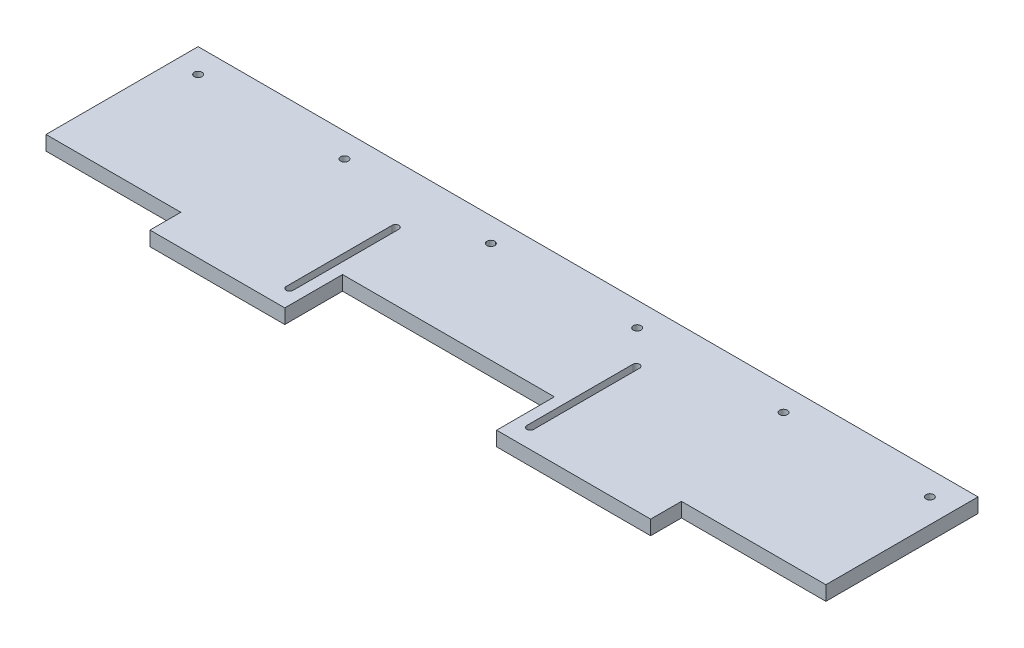
SolidWorks part; units mm, degrees
material "Acrylic (Medium-high impact)"
ref_plane "Front Plane" through (0, 0, 0) normal (0, 0, 1) x (1, 0, 0)
ref_plane "Top Plane" through (0, 0, 0) normal (0, 1, 0) x (1, 0, 0)
ref_plane "Right Plane" through (0, 0, 0) normal (1, 0, 0) x (0, 0, -1)
sketch "Sketch1" plane through (0, 0, 0) normal (0, 1, 0) x (1, 0, 0)
  line L1 (-250.825, -28.575) -> (250.825, -28.575)
  line L2 (-250.825, -28.575) -> (-250.825, 28.575)
  line L3 (-250.825, 28.575) -> (250.825, 28.575)
  line L4 (250.825, -28.575) -> (250.825, 28.575)
  line L5 (-250.825, -28.575) -> (250.825, 28.575) construction
  line L6 (-250.825, 28.575) -> (250.825, -28.575) construction
  line L7 (174.625, -28.575) -> (-28.575, -28.575)
  line L11 (-282.575, -28.575) -> (-130.175, -28.575)
  point P0 (0, 0)
  dimension "D1" = 501.65
  dimension "D2" = 57.15
extrude "Boss-Extrude1" add sketch "Sketch1" along normal mid plane 9.525 contours L1 L4 L3 L2
sketch "Sketch2" plane through (0, 0, 0) normal (0, 1, 0) x (1, 0, 0)
  line L0 (-250.825, -28.575) -> (250.825, -28.575) construction
  line L1 (161.925, -28.575) -> (60.325, -28.575)
  line L2 (161.925, -28.575) -> (161.925, -92.075)
  line L3 (161.925, -92.075) -> (60.325, -92.075)
  line L4 (60.325, -28.575) -> (60.325, -92.075)
  line L5 (0, -5.2388) -> (0, 5.2388) construction
  line L6 (-79.375, -28.575) -> (-168.275, -28.575)
  line L7 (-79.375, -28.575) -> (-79.375, -92.075)
  line L8 (-79.375, -92.075) -> (-168.275, -92.075)
  line L9 (-168.275, -28.575) -> (-168.275, -92.075)
  line L10 (250.825, -28.575) -> (250.825, 28.575) construction
  line L11 (-250.825, -28.575) -> (-250.825, 28.575) construction
  line L12 (-250.825, 28.575) -> (250.825, 28.575) construction
  line L13 (250.825, -28.575) -> (250.825, 28.575) construction
  line L14 (161.925, -28.575) -> (250.825, -28.575)
  line L15 (161.925, -28.575) -> (161.925, -71.755)
  line L16 (161.925, -71.755) -> (250.825, -71.755)
  line L17 (250.825, -28.575) -> (250.825, -71.755)
  line L18 (-250.825, -28.575) -> (-250.825, 28.575) construction
  line L19 (-79.375, -28.575) -> (60.325, -28.575)
  line L20 (-79.375, -28.575) -> (-79.375, -53.975)
  line L21 (-79.375, -53.975) -> (60.325, -53.975)
  line L22 (60.325, -28.575) -> (60.325, -53.975)
  line L23 (-168.275, -28.575) -> (-250.825, -28.575)
  line L24 (-168.275, -28.575) -> (-168.275, -71.755)
  line L25 (-168.275, -71.755) -> (-250.825, -71.755)
  line L26 (-250.825, -28.575) -> (-250.825, -71.755)
  point P19 (60.325, -92.075)
  dimension "D1" = 139.7
  dimension "D2" = 88.9
  dimension "D3" = 82.55
  dimension "D4" = 79.375
  dimension "D5" = 120.65
  dimension "D6" = 43.18
  dimension "D7" = 25.4
  dimension "D8" = 43.18
extrude "Boss-Extrude2" add sketch "Sketch2" along normal mid plane 9.525 contours L6 L9 L8 L7 | L23 L26 L25 L9 | L7 L21 L4 L19 | L17 L14 L2 L16
sketch "Sketch3" [suppressed] plane through (0, 4.7625, 0) normal (0, 1, 0) x (1, 0, 0)
  line L0 (-149.225, 247.65) -> (149.225, 247.65) construction
  line L1 (-98.425, 12.7) -> (98.425, 12.7)
  line L2 (-98.425, 12.7) -> (-98.425, -101.6)
  line L3 (-98.425, -101.6) -> (98.425, -101.6)
  line L4 (98.425, 12.7) -> (98.425, -101.6)
  line L5 (-98.425, 12.7) -> (98.425, -101.6) construction
  line L6 (-98.425, -101.6) -> (98.425, 12.7) construction
  line L7 (-149.225, -247.65) -> (149.225, -247.65) construction
  point P0 (0, -44.45)
  point P7 (0, 247.65)
  point P8 (0, 12.7)
  dimension "D1" = 196.85
  dimension "D2" = 114.3
  dimension "D3" = 203.2
extrude "Cut-Extrude1" [suppressed] cut sketch "Sketch3" against normal through all and the other way through all
sketch "Sketch4" [suppressed] plane through (0, -4.7625, 0) normal (0, -1, 0) x (1, 0, 0)
  line L0 (-107.315, 31.75) -> (107.315, 31.75) construction
  line L1 (-107.315, 33.9979) -> (107.315, 33.9979)
  line L2 (-107.315, 29.5021) -> (107.315, 29.5021)
  line L3 (-107.315, 6.35) -> (107.315, 6.35) construction
  line L4 (-107.315, 8.5979) -> (107.315, 8.5979)
  line L5 (-107.315, 4.1021) -> (107.315, 4.1021)
  arc A0 (-107.315, 33.9979) -> (-107.315, 29.5021) centre (-107.315, 31.75) ccw
  arc A1 (107.315, 29.5021) -> (107.315, 33.9979) centre (107.315, 31.75) ccw
  arc A2 (-107.315, 8.5979) -> (-107.315, 4.1021) centre (-107.315, 6.35) ccw
  arc A3 (107.315, 4.1021) -> (107.315, 8.5979) centre (107.315, 6.35) ccw
  point P0 (-107.315, 31.75)
  point P1 (107.315, 31.75)
  point P3 (107.315, 6.35)
  point P5 (-107.315, 6.35)
  point P10 (0, 31.75)
  point P15 (0, 6.35)
  dimension "D1" = 4.4958
  dimension "D2" = 4.4958
extrude "Cut-Extrude2" [suppressed] cut sketch "Sketch4" against normal through all
sketch "Sketch5" plane through (0, -4.7625, 0) normal (0, -1, 0) x (1, 0, 0)
  line L0 (69.85, 79.375) -> (69.85, -9.525) construction
  line L1 (60.325, 53.975) -> (60.325, 92.075) construction
  line L2 (161.925, 92.075) -> (60.325, 92.075) construction
  line L3 (-247.65, -22.225) -> (247.65, -22.225) construction
  line L4 (69.85, 79.375) -> (69.85, -9.525) construction
  line L5 (72.0979, 79.375) -> (72.0979, -9.525)
  line L6 (67.6021, 79.375) -> (67.6021, -9.525)
  line L7 (-88.9, 79.375) -> (-88.9, -9.525) construction
  line L8 (-79.375, 53.975) -> (-79.375, 92.075) construction
  line L9 (-79.375, 92.075) -> (-168.275, 92.075) construction
  line L10 (-88.9, 79.375) -> (-88.9, -9.525) construction
  line L11 (-86.6521, 79.375) -> (-86.6521, -9.525)
  line L12 (-91.1479, 79.375) -> (-91.1479, -9.525)
  arc A0 (72.0979, 79.375) -> (67.6021, 79.375) centre (69.85, 79.375) ccw
  arc A1 (67.6021, -9.525) -> (72.0979, -9.525) centre (69.85, -9.525) ccw
  arc A2 (-86.6521, 79.375) -> (-91.1479, 79.375) centre (-88.9, 79.375) ccw
  arc A3 (-91.1479, -9.525) -> (-86.6521, -9.525) centre (-88.9, -9.525) ccw
  point P8 (69.85, 34.925)
  point P19 (-88.9, 34.925)
  dimension "D1" = 9.525
  dimension "D2" = 12.7
  dimension "D3" = 12.7
  dimension "D4" = 4.4958
  dimension "D5" = 9.525
  dimension "D6" = 12.7
  dimension "D7" = 12.7
  dimension "D8" = 4.4958
extrude "Cut-Extrude3" [suppressed] cut sketch "Sketch5" against normal through all contours L12 A3 L11 A2 | L6 A1 L5 A0
sketch "Sketch6" [suppressed] plane through (0, 3.175, 0) normal (0, 1, 0) x (1, 0, 0)
  line L0 (-79.375, -38.1) -> (-79.375, 38.1) construction
  line L1 (-88.9, -50.8) -> (-88.9, 50.8) construction
  line L2 (-88.9, -50.8) -> (88.9, -50.8) construction
  line L3 (-88.9, 50.8) -> (88.9, 50.8) construction
  line L4 (79.375, -38.1) -> (79.375, 38.1) construction
  line L5 (88.9, -50.8) -> (88.9, 50.8) construction
  line L6 (-79.375, -38.1) -> (-79.375, 38.1) construction
  line L7 (-81.6229, -38.1) -> (-81.6229, 38.1)
  line L8 (-77.1271, -38.1) -> (-77.1271, 38.1)
  line L9 (79.375, -38.1) -> (79.375, 38.1) construction
  line L10 (77.1271, -38.1) -> (77.1271, 38.1)
  line L11 (81.6229, -38.1) -> (81.6229, 38.1)
  arc A0 (-81.6229, -38.1) -> (-77.1271, -38.1) centre (-79.375, -38.1) ccw
  arc A1 (-77.1271, 38.1) -> (-81.6229, 38.1) centre (-79.375, 38.1) ccw
  arc A2 (77.1271, -38.1) -> (81.6229, -38.1) centre (79.375, -38.1) ccw
  arc A3 (81.6229, 38.1) -> (77.1271, 38.1) centre (79.375, 38.1) ccw
  point P12 (-79.375, 0)
  point P17 (79.375, 0)
  dimension "D1" = 9.525
  dimension "D2" = 12.7
  dimension "D3" = 12.7
  dimension "D4" = 9.525
  dimension "D5" = 12.7
  dimension "D6" = 12.7
  dimension "D7" = 4.4958
  dimension "D8" = 4.4958
extrude "Cut-Extrude4" [suppressed] cut sketch "Sketch6" against normal through all
sketch "Sketch7" [suppressed] plane through (0, 4.7625, 0) normal (0, 1, 0) x (1, 0, 0)
  point P0 (115.1313, 66.802)
  point P1 (139.827, 42.1063)
  point P3 (-139.827, 42.1063)
  point P5 (-115.1313, 66.802)
hole_wizard "#12 Clearance Hole1" [suppressed] positions "Sketch8" profile "Sketch9" hole size "#12" standard "ANSI Inch"
sketch "Sketch8" plane through (0, 4.7625, 0) normal (0, 1, 0) x (1, 0, 0)
  point P0 (-139.827, 42.1063)
  point P3 (-115.1313, 66.802)
  point P6 (115.1313, 66.802)
  point P9 (139.827, 42.1063)
sketch "Sketch9" plane through (-139.827, 4.7625, -42.1063) normal (1, 0, 0) x (0, 0, 1)
  line L0 (0, 0) -> (0, 18.1964)
  line L1 (0, 18.1964) -> (2.8067, 16.51)
  line L2 (2.8067, 16.51) -> (2.8067, 0)
  line L5 (2.8067, 0) -> (0, 0)
  line L10 (0, 18.1964) -> (-2.8067, 16.51) construction
  line L11 (0, -6.35) -> (0, 107.95) construction
  dimension "Hole Dia." = 5.6134
  dimension "Hole Depth" = 16.51
  dimension "Drill Angle" = 118
sketch "Sketch10" [suppressed] plane through (0, -4.7625, 0) normal (0, -1, 0) x (1, 0, 0)
  point P0 (223.8375, -6.35)
  point P1 (223.8375, 19.05)
  point P3 (-223.8375, 19.05)
  point P5 (-223.8375, -6.35)
hole_wizard "#12 Clearance Hole3" [suppressed] positions "Sketch11" profile "Sketch12" hole size "#12" standard "ANSI Inch"
sketch "Sketch11" [suppressed] plane through (0, -4.7625, 0) normal (0, -1, 0) x (-1, 0, 0)
  point P0 (-223.8375, -19.05)
  point P3 (-223.8375, 6.35)
  point P6 (223.8375, -19.05)
  point P9 (223.8375, 6.35)
sketch "Sketch12" plane through (223.8375, -4.7625, 19.05) normal (1, 0, 0) x (0, 0, -1)
  line L0 (0, 0) -> (0, 18.1964)
  line L1 (0, 18.1964) -> (2.8067, 16.51)
  line L2 (2.8067, 16.51) -> (2.8067, 0)
  line L5 (2.8067, 0) -> (0, 0)
  line L10 (0, 18.1964) -> (-2.8067, 16.51) construction
  line L11 (0, -6.35) -> (0, 107.95) construction
  dimension "Hole Dia." = 5.6134
  dimension "Hole Depth" = 16.51
  dimension "Drill Angle" = 118
sketch "Sketch13" [suppressed] plane through (0, -4.7625, 0) normal (0, -1, 0) x (1, 0, 0)
  point P0 (133.35, -223.8375)
  point P1 (107.95, -223.8375)
  point P3 (-107.95, -223.8375)
  point P5 (-133.35, -223.8375)
  point P7 (133.35, 223.8375)
  point P9 (107.95, 223.8375)
  point P11 (-107.95, 223.8375)
  point P13 (-133.35, 223.8375)
hole_wizard "#12 Clearance Hole2" [suppressed] positions "Sketch14" profile "Sketch15" hole size "#12" standard "ANSI Inch"
sketch "Sketch14" plane through (0, -4.7625, 0) normal (0, -1, 0) x (-1, 0, 0)
  point P0 (107.95, -223.8375)
  point P3 (133.35, -223.8375)
  point P6 (133.35, 223.8375)
  point P9 (107.95, 223.8375)
  point P12 (-133.35, 223.8375)
  point P15 (-107.95, 223.8375)
  point P18 (-133.35, -223.8375)
  point P21 (-107.95, -223.8375)
sketch "Sketch15" plane through (-107.95, -4.7625, 223.8375) normal (1, 0, 0) x (0, 0, -1)
  line L0 (0, 0) -> (0, 18.1964)
  line L1 (0, 18.1964) -> (2.8067, 16.51)
  line L2 (2.8067, 16.51) -> (2.8067, 0)
  line L5 (2.8067, 0) -> (0, 0)
  line L10 (0, 18.1964) -> (-2.8067, 16.51) construction
  line L11 (0, -6.35) -> (0, 107.95) construction
  dimension "Hole Dia." = 5.6134
  dimension "Hole Depth" = 16.51
  dimension "Drill Angle" = 118
sketch "Sketch16" [suppressed] plane through (0, 3.175, 0) normal (0, 1, 0) x (1, 0, 0)
  line L0 (88.9, -50.8) -> (88.9, 50.8) construction
  line L1 (-88.9, -50.8) -> (-88.9, 50.8) construction
  line L2 (-88.9, -50.8) -> (88.9, -50.8) construction
  point P0 (79.375, -38.1)
  point P1 (-79.375, -38.1)
  dimension "D1" = 9.525
  dimension "D2" = 9.525
  dimension "D3" = 12.7
hole_wizard "#8 Clearance Hole1" [suppressed] positions "Sketch17" profile "Sketch19" hole size "#8" standard "ANSI Inch"
sketch "Sketch17" plane through (0, 3.175, 0) normal (0, 1, 0) x (1, 0, 0)
  point P0 (79.375, -38.1)
  point P3 (-79.375, -38.1)
sketch "Sketch19" plane through (79.375, 3.175, 38.1) normal (1, 0, 0) x (0, 0, 1)
  line L0 (0, 0) -> (0, 12.0187)
  line L1 (0, 12.0187) -> (2.2479, 10.668)
  line L2 (2.2479, 10.668) -> (2.2479, 0)
  line L5 (2.2479, 0) -> (0, 0)
  line L10 (0, 12.0187) -> (-2.2479, 10.668) construction
  line L11 (0, -6.35) -> (0, 107.95) construction
  dimension "Hole Dia." = 4.4958
  dimension "Hole Depth" = 10.668
  dimension "Drill Angle" = 118
sketch "Sketch20" [suppressed] plane through (0, -4.7625, 0) normal (0, -1, 0) x (1, 0, 0)
  line L0 (-149.225, 247.65) -> (149.225, 247.65) construction
  line L1 (23.9395, 147.5105) -> (-23.9395, 147.5105)
  line L2 (23.9395, 147.5105) -> (23.9395, 195.3895)
  line L3 (23.9395, 195.3895) -> (-23.9395, 195.3895)
  line L4 (-23.9395, 147.5105) -> (-23.9395, 195.3895)
  line L5 (23.9395, 147.5105) -> (-23.9395, 195.3895) construction
  line L6 (23.9395, 195.3895) -> (-23.9395, 147.5105) construction
  line L8 (38.1, 155.575) -> (-38.1, 155.575) construction
  line L9 (38.1, 155.575) -> (38.1, 187.325) construction
  line L10 (38.1, 187.325) -> (-38.1, 187.325) construction
  line L11 (-38.1, 155.575) -> (-38.1, 187.325) construction
  point P0 (0, 171.45)
  point P7 (0, 247.65)
  point P8 (38.1, 155.575)
  point P9 (38.1, 187.325)
  point P10 (-38.1, 155.575)
  point P11 (-38.1, 187.325)
  point P18 (0, 187.325)
  point P19 (0, 195.3895)
  point P20 (-38.1, 171.45)
  point P21 (-23.9395, 171.45)
  dimension "D1" = 47.879
  dimension "D2" = 47.879
  dimension "D3" = 38.1
  dimension "D4" = 15.875
  dimension "D5" = 76.2
extrude "Cut-Extrude5" [suppressed] cut sketch "Sketch20" against normal through all contours L1 L4 L3 L2
hole_wizard "#10 Clearance Hole1" [suppressed] positions "Sketch21" profile "Sketch22" hole size "#10" standard "ANSI Inch"
sketch "Sketch21" plane through (0, -4.7625, 0) normal (0, -1, 0) x (-1, 0, 0)
  point P0 (-38.1, -155.575)
  point P3 (38.1, -155.575)
  point P6 (38.1, -187.325)
  point P9 (-38.1, -187.325)
sketch "Sketch22" plane through (38.1, -4.7625, 155.575) normal (1, 0, 0) x (0, 0, -1)
  line L0 (0, 0) -> (0, 12.2018)
  line L1 (0, 12.2018) -> (2.5527, 10.668)
  line L2 (2.5527, 10.668) -> (2.5527, 0)
  line L5 (2.5527, 0) -> (0, 0)
  line L10 (0, 12.2018) -> (-2.5527, 10.668) construction
  line L11 (0, -6.35) -> (0, 107.95) construction
  dimension "Hole Dia." = 5.1054
  dimension "Hole Depth" = 10.668
  dimension "Drill Angle" = 118
sketch "Sketch23" plane through (-250.825, 0, 0) normal (-1, 0, 0) x (0, 0, 1)
  line L4 (-28.575, -4.7625) -> (71.755, -4.7625)
  line L5 (71.755, -4.7625) -> (71.755, 4.7625)
  line L6 (71.755, 4.7625) -> (-28.575, 4.7625)
  line L7 (-28.575, 4.7625) -> (-28.575, -4.7625)
  line L8 (-28.575, -4.7625) -> (71.755, -4.7625)
  line L9 (71.755, -4.7625) -> (71.755, 4.7625)
  line L10 (71.755, 4.7625) -> (-28.575, 4.7625)
  line L11 (-28.575, 4.7625) -> (-28.575, -4.7625)
  dimension "D1" = 0
extrude "Boss-Extrude3" add sketch "Sketch23" along normal blind 6.35
mirror "Mirror1" about plane through (0, 0, 0) normal (1, 0, 0) of "Boss-Extrude3"
sketch "Sketch27" plane through (0, 4.7625, 0) normal (0, 1, 0) x (1, 0, 0)
  line L1 (257.175, -71.755) -> (257.175, 28.575) construction
  line L2 (-257.175, 28.575) -> (257.175, 28.575) construction
  point P0 (241.3, 12.7)
  dimension "D1" = 15.875
  dimension "D2" = 15.875
hole_wizard "#10 Clearance Hole2" positions "Sketch28" profile "Sketch30" hole size "#10" standard "ANSI Inch" end condition up to next
sketch "Sketch28" plane through (0, 4.7625, 0) normal (0, 1, 0) x (1, 0, 0)
  point P0 (241.3, 12.7)
sketch "Sketch30" plane through (241.3, 4.7625, -12.7) normal (1, 0, 0) x (0, 0, 1)
  line L0 (0, 0) -> (0, 9.525)
  line L1 (0, 9.525) -> (2.5527, 9.525)
  line L2 (2.5527, 9.525) -> (2.5527, 0)
  line L5 (2.5527, 0) -> (0, 0)
  line L11 (0, -6.35) -> (0, 107.95) construction
  dimension "Thru Hole Dia." = 5.1054
  dimension "Thru Hole Depth" = 9.525
pattern_linear "LPattern1" count 6 spacing 96.52 along (-1, 0, 0) of "#10 Clearance Hole2"
sketch "Sketch31" [suppressed] plane through (0, 4.7625, 0) normal (0, 1, 0) x (1, 0, 0)
  line L1 (0, -5.2388) -> (0, 5.2388) construction
  line L2 (-149.225, 76.2) -> (149.225, 76.2) construction
  point P0 (-95.25, 60.325)
  dimension "D1" = 15.875
  dimension "D2" = 95.25
hole_wizard "#10 Clearance Hole3" [suppressed] positions "Sketch32" profile "Sketch33" hole size "#10" standard "ANSI Inch"
sketch "Sketch32" plane through (0, 4.7625, 0) normal (0, 1, 0) x (1, 0, 0)
  point P0 (-95.25, 60.325)
sketch "Sketch33" plane through (-95.25, 4.7625, -60.325) normal (1, 0, 0) x (0, 0, 1)
  line L0 (0, 0) -> (0, 9.525)
  line L1 (0, 9.525) -> (2.5527, 9.525)
  line L2 (2.5527, 9.525) -> (2.5527, 0)
  line L5 (2.5527, 0) -> (0, 0)
  line L11 (0, -6.35) -> (0, 107.95) construction
  dimension "Thru Hole Dia." = 5.1054
  dimension "Thru Hole Depth" = 9.525
pattern_linear "LPattern2" [suppressed] count 4 spacing 63.5
sketch "Sketch34" [suppressed] plane through (0, 4.7625, 0) normal (0, 1, 0) x (1, 0, 0)
  line L0 (0, -5.2388) -> (0, 5.2388) construction
  line L1 (-149.225, 247.65) -> (149.225, 247.65) construction
  point P0 (-63.5, 241.3)
  dimension "D1" = 63.5
  dimension "D2" = 6.35
hole_wizard "#10 Clearance Hole4" [suppressed] positions "Sketch35" profile "Sketch36" hole size "#10" standard "ANSI Inch"
sketch "Sketch35" plane through (0, 4.7625, 0) normal (0, 1, 0) x (1, 0, 0)
  point P0 (-63.5, 241.3)
sketch "Sketch36" plane through (-63.5, 4.7625, -241.3) normal (1, 0, 0) x (0, 0, 1)
  line L0 (0, 0) -> (0, 9.525)
  line L1 (0, 9.525) -> (2.5527, 9.525)
  line L2 (2.5527, 9.525) -> (2.5527, 0)
  line L5 (2.5527, 0) -> (0, 0)
  line L11 (0, -6.35) -> (0, 107.95) construction
  dimension "Thru Hole Dia." = 5.1054
  dimension "Thru Hole Depth" = 9.525
pattern_linear "LPattern3" [suppressed] count 3 spacing 63.5
mirror "Mirror2" [suppressed] about plane through (0, 0, 0) normal (0, 0, 1)
sketch "Sketch37" [suppressed] plane through (0, 4.7625, 0) normal (0, 1, 0) x (1, 0, 0)
  line L0 (-5.2388, 0) -> (5.2388, 0) construction
  line L1 (-149.225, -247.65) -> (-149.225, 247.65) construction
  point P0 (-142.875, 0)
  dimension "D1" = 6.35
hole_wizard "#10 Clearance Hole5" [suppressed] positions "Sketch38" profile "Sketch39" hole size "#10" standard "ANSI Inch"
sketch "Sketch38" plane through (0, 4.7625, 0) normal (0, 1, 0) x (1, 0, 0)
  point P0 (-142.875, 0)
sketch "Sketch39" plane through (-142.875, 4.7625, 0) normal (1, 0, 0) x (0, 0, 1)
  line L0 (0, 0) -> (0, 9.525)
  line L1 (0, 9.525) -> (2.5527, 9.525)
  line L2 (2.5527, 9.525) -> (2.5527, 0)
  line L5 (2.5527, 0) -> (0, 0)
  line L11 (0, -6.35) -> (0, 107.95) construction
  dimension "Thru Hole Dia." = 5.1054
  dimension "Thru Hole Depth" = 9.525
pattern_linear "LPattern4" [suppressed] count 3 spacing 96.52 count 3 spacing 96.52
mirror "Mirror3" [suppressed] about plane through (0, 0, 0) normal (1, 0, 0)
sketch "Sketch40" plane through (0, 4.7625, 0) normal (0, 1, 0) x (1, 0, 0)
  line L0 (-79.375, -53.975) -> (-79.375, -92.075) construction
  line L3 (-88.9, -79.375) -> (-88.9, -9.525) construction
  line L4 (-91.1479, -79.375) -> (-91.1479, -9.525)
  line L5 (-86.6521, -79.375) -> (-86.6521, -9.525)
  line L6 (69.85, -79.375) -> (69.85, -9.525) construction
  line L7 (67.6021, -79.375) -> (67.6021, -9.525)
  line L8 (72.0979, -79.375) -> (72.0979, -9.525)
  line L9 (60.325, -53.975) -> (60.325, -92.075) construction
  line L12 (-79.375, -92.075) -> (-168.275, -92.075) construction
  line L13 (161.925, -92.075) -> (60.325, -92.075) construction
  arc A2 (-91.1479, -79.375) -> (-86.6521, -79.375) centre (-88.9, -79.375) ccw
  arc A3 (-86.6521, -9.525) -> (-91.1479, -9.525) centre (-88.9, -9.525) ccw
  arc A4 (67.6021, -79.375) -> (72.0979, -79.375) centre (69.85, -79.375) ccw
  arc A5 (72.0979, -9.525) -> (67.6021, -9.525) centre (69.85, -9.525) ccw
  point P7 (-88.9, -44.45)
  point P14 (69.85, -44.45)
  dimension "D1" = 9.525
  dimension "D2" = 4.4958
  dimension "D3" = 4.4958
  dimension "D4" = 9.525
  dimension "D5" = 12.7
  dimension "D6" = 12.7
  dimension "D7" = 69.85
  dimension "D8" = 69.85
extrude "Cut-Extrude6" cut sketch "Sketch40" against normal up to next
sketch "Sketch41" [suppressed] plane through (0, -4.7625, 0) normal (0, -1, 0) x (1, 0, 0)
  point P0 (120.65, -39.4255)
  point P1 (-120.65, -39.4255)
  point P3 (-120.65, 128.3255)
  point P5 (120.65, 128.3255)
hole_wizard "#10 Clearance Hole6" [suppressed] positions "Sketch42" profile "Sketch43" hole size "#10" standard "ANSI Inch"
sketch "Sketch42" plane through (0, 4.7625, 0) normal (0, 1, 0) x (1, 0, 0)
  point P0 (120.65, 39.4255)
  point P3 (120.65, -128.3255)
  point P6 (-120.65, -128.3255)
  point P9 (-120.65, 39.4255)
sketch "Sketch43" plane through (120.65, 4.7625, -39.4255) normal (1, 0, 0) x (0, 0, 1)
  line L0 (0, 0) -> (0, 9.525)
  line L1 (0, 9.525) -> (2.5527, 9.525)
  line L2 (2.5527, 9.525) -> (2.5527, 0)
  line L5 (2.5527, 0) -> (0, 0)
  line L11 (0, -6.35) -> (0, 107.95) construction
  dimension "Thru Hole Dia." = 5.1054
  dimension "Thru Hole Depth" = 9.525
